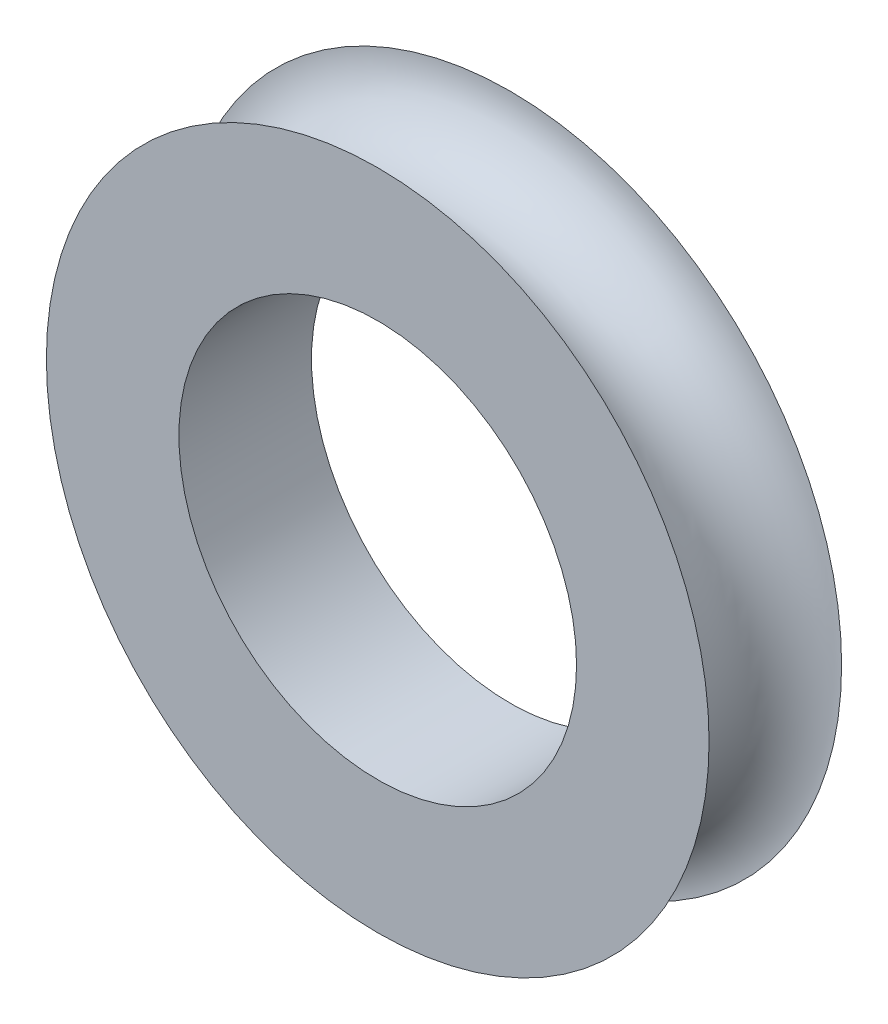
SolidWorks part; units mm, degrees
ref_plane "Front Plane" through (0, 0, 0) normal (0, 0, 1) x (1, 0, 0)
ref_plane "Top Plane" through (0, 0, 0) normal (0, 1, 0) x (1, 0, 0)
ref_plane "Right Plane" through (0, 0, 0) normal (1, 0, 0) x (0, 0, -1)
sketch "Sketch1" plane through (0, 0, 0) normal (0, 0, 1) x (1, 0, 0)
  circle A0 centre (0, 0) radius 5
  circle A1 centre (0, 0) radius 3
  dimension "D1" = 10
  dimension "D2" = 6
extrude "Boss-Extrude1" add sketch "Sketch1" along normal blind 2
sketch "Sketch2" plane through (0, 0, 0) normal (1, 0, 0) x (0, 0, -1)
  line L0 (0, 5) -> (-2, 5) construction
  line L1 (-2, 5) -> (0, 5)
  arc A0 (-2, 5) -> (0, 5) centre (-1, 5) ccw
revolve "Cut-Revolve1" cut sketch "Sketch2" angle 360 about axis through (0, 0, 2) along (0, 0, -1)
ref_point "Centre"
equation "\"CableDiameter\"=2"
equation "\"D1@Boss-Extrude1\"=\"CableDiameter\""
